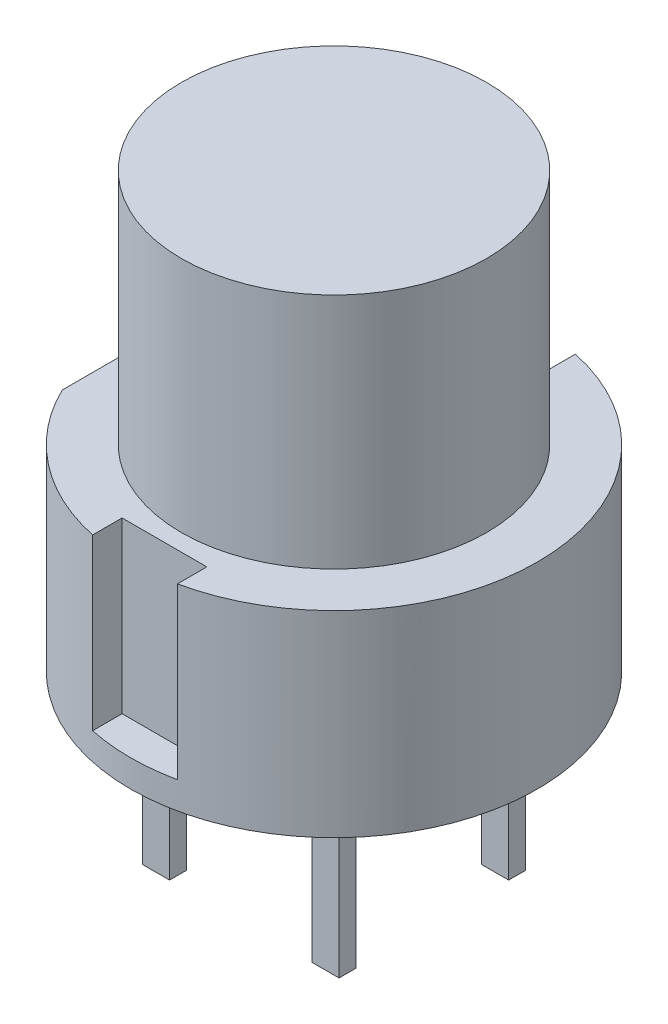
SolidWorks part; units mm, degrees
ref_plane "Front" through (0, 0, 0) normal (0, 0, 1) x (1, 0, 0)
ref_plane "Top" through (0, 0, 0) normal (0, 1, 0) x (1, 0, 0)
ref_plane "Right" through (0, 0, 0) normal (1, 0, 0) x (0, 0, -1)
sketch "Sketch1" plane through (0, 0, 0) normal (0, 0, 1) x (1, 0, 0)
  line L0 (0, 33.1829) -> (0, -33.3926) construction
  line L1 (0, 0) -> (2, 0)
  line L2 (2, 0) -> (2, 1.5)
  line L3 (2, 1.5) -> (6, 1.5)
  line L4 (6, 1.5) -> (6, 7.3)
  line L5 (6, 7.3) -> (4.5, 7.3)
  line L6 (4.5, 7.3) -> (4.5, 14.3)
  line L7 (4.5, 14.3) -> (0, 14.3)
  line L8 (0, 14.3) -> (0, 0)
  dimension "D1" = 2
  dimension "D2" = 1.5
  dimension "D3" = 6
  dimension "D4" = 5.8
  dimension "D5" = 7
  dimension "D6" = 4.5
revolve "Revolve1" add sketch "Sketch1" angle 360 about L0
sketch "Sketch2" plane through (0, 1.5, 0) normal (0, -1, 0) x (1, 0, 0)
  line L0 (0, 0) -> (-2.5, 2.5) construction
  line L1 (-2.9, 2.25) -> (-2.1, 2.25)
  line L2 (-2.9, 2.25) -> (-2.9, 2.75)
  line L3 (-2.9, 2.75) -> (-2.1, 2.75)
  line L4 (-2.1, 2.25) -> (-2.1, 2.75)
  line L5 (-2.9, 2.25) -> (-2.1, 2.75) construction
  line L6 (-2.9, 2.75) -> (-2.1, 2.25) construction
  line L7 (0, 0) -> (-4.5777, 0) construction
  line L8 (0, 0) -> (0, 4.3843) construction
  line L9 (2.9, 2.25) -> (2.1, 2.25)
  line L10 (2.1, 2.25) -> (2.1, 2.75)
  line L11 (2.9, 2.75) -> (2.1, 2.75)
  line L12 (2.9, 2.25) -> (2.9, 2.75)
  line L13 (2.9, -2.25) -> (2.9, -2.75)
  line L14 (2.9, -2.25) -> (2.1, -2.25)
  line L15 (2.1, -2.25) -> (2.1, -2.75)
  line L16 (2.9, -2.75) -> (2.1, -2.75)
  line L17 (-2.9, -2.25) -> (-2.9, -2.75)
  line L18 (-2.9, -2.25) -> (-2.1, -2.25)
  line L19 (-2.1, -2.25) -> (-2.1, -2.75)
  line L20 (-2.9, -2.75) -> (-2.1, -2.75)
  point P0 (-2.5, 2.5)
  point P1 (-2.5, 2.5)
  dimension "D1" = 0.8
  dimension "D2" = 0.5
  dimension "D3" = 45
  dimension "D4" = 2.5
extrude "Legs" add sketch "Sketch2" along normal blind 5
sketch "Sketch3" plane through (0, 14.3, 0) normal (0, 1, 0) x (1, 0, 0)
  line L1 (-10, 6.4338) -> (-5.4, 6.4338)
  line L2 (-10, 6.4338) -> (-10, -7.3098)
  line L3 (-10, -7.3098) -> (-5.4, -7.3098)
  line L4 (-5.4, 6.4338) -> (-5.4, -7.3098)
  line L5 (-10, 6.4338) -> (-5.4, -7.3098) construction
  line L6 (-10, -7.3098) -> (-5.4, 6.4338) construction
  circle A0 centre (0, 0) radius 6 construction
  point P0 (-7.7, -0.438)
  dimension "D1" = 10
  dimension "D2" = 5.4
extrude "Extrude3" cut sketch "Sketch3" against normal through all
sketch "Sketch4" plane through (0, 7.3, 0) normal (0, 1, 0) x (1, 0, 0)
  line L0 (-2.157, 0) -> (3.6983, 0) construction
  line L1 (-1.25, 5) -> (1.25, 5)
  line L2 (-1.25, 5) -> (-1.25, 7)
  line L3 (-1.25, 7) -> (1.25, 7)
  line L4 (1.25, 5) -> (1.25, 7)
  line L5 (-1.25, 5) -> (1.25, 7) construction
  line L6 (-1.25, 7) -> (1.25, 5) construction
  line L7 (-1.25, -5) -> (-1.25, -7)
  line L8 (-1.25, -7) -> (1.25, -7)
  line L9 (1.25, -5) -> (1.25, -7)
  line L10 (-1.25, -5) -> (1.25, -5)
  point P0 (0, 6)
  dimension "D1" = 6
  dimension "D2" = 2
  dimension "D3" = 2.5
extrude "Extrude4" cut sketch "Sketch4" against normal blind 5
